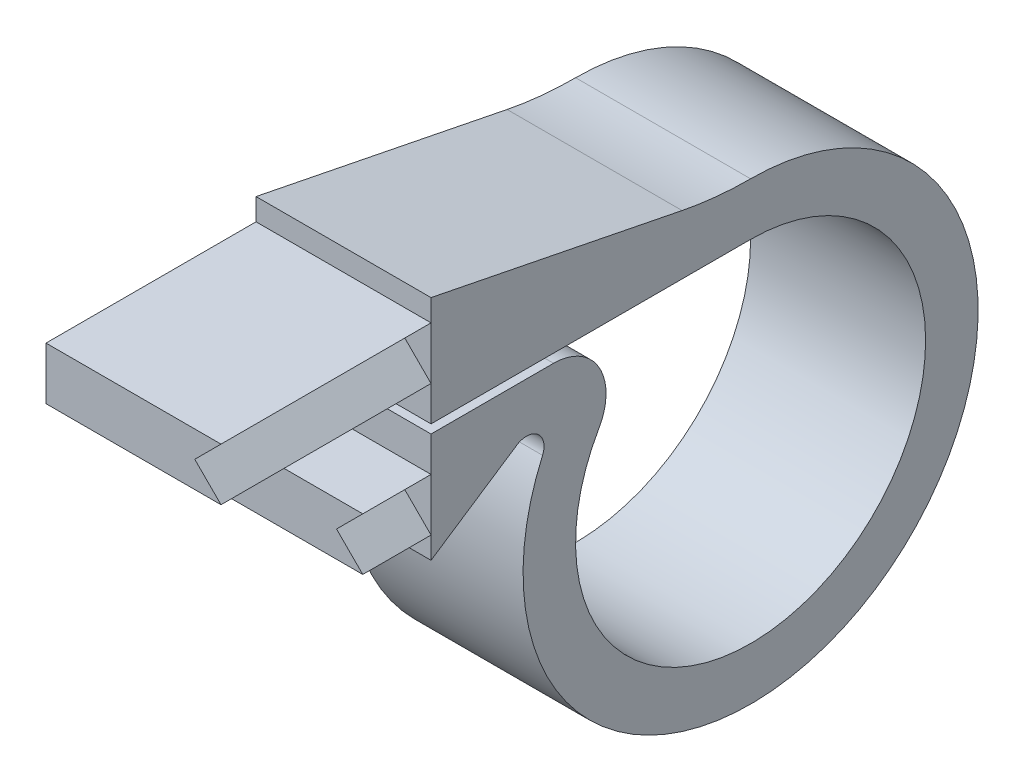
SolidWorks part; units mm, degrees
ref_plane "Front Plane" through (0, 0, 0) normal (0, 0, 1) x (1, 0, 0)
ref_plane "Top Plane" through (0, 0, 0) normal (0, 1, 0) x (1, 0, 0)
ref_plane "Right Plane" through (0, 0, 0) normal (1, 0, 0) x (0, 0, -1)
sketch "Sketch1" plane through (0, 0, 0) normal (1, 0, 0) x (0, 0, -1)
  line L0 (-11.2583, -0.5) -> (-18.2583, -0.5)
  line L1 (0, 0) -> (-18.2583, 0)
  line L6 (-3.915, 3.3869) -> (-18.2583, 6.25)
  line L7 (-18.2583, 6.25) -> (-18.2583, 0)
  line L9 (-18.2583, -6.75) -> (-13.3544, -3.5)
  line L10 (-18.2583, -6.75) -> (-18.2583, -0.5)
  arc A0 (0, 0) -> (-8.6603, -5) centre (0, -10) cw
  arc A1 (0, 3) -> (-11.8876, -4.7383) centre (0, -10) cw
  arc A2 (-8.6603, -5) -> (-11.2583, -0.5) centre (-11.2583, -3.5) ccw
  arc A3 (-11.8876, -4.7383) -> (-13.3544, -3.5) centre (-12.802, -4.3336) ccw
  arc A4 (0, 3) -> (-3.915, 3.3869) centre (0, 23) cw
  dimension "D1" = 3
  dimension "D4" = 3
  dimension "D5" = 1
  dimension "D6" = 10
  dimension "D3" = 20
  dimension "D11" = 3
  dimension "D2" = 7
  dimension "D7" = 0.5
  dimension "D8" = 6.25
  dimension "D9" = 6.25
  dimension "D10" = 3
extrude "Boss-Extrude1" add sketch "Sketch1" along normal blind 10
sketch "Sketch2" plane through (0, 0, 18.2583) normal (0, 0, 1) x (1, 0, 0)
  line L2 (10, -0.5) -> (10, -6.75) construction
  line L3 (10, 6.25) -> (10, 0) construction
  line L5 (10, -0.5) -> (0, -0.5) construction
  line L6 (0, 2) -> (10, 2)
  line L7 (0, 6.25) -> (0, 0) construction
  line L8 (0, -0.5) -> (0, -6.75) construction
  line L11 (10, 5) -> (0, 5)
  line L12 (0, 5) -> (0, 2)
  line L14 (10, 5) -> (8.5, 3.5)
  line L15 (8.5, 3.5) -> (10, 2)
  line L16 (10, 0) -> (0, 0) construction
  line L17 (0, -5.5) -> (10, -5.5)
  line L18 (10, -2.5) -> (0, -2.5)
  line L19 (0, -2.5) -> (0, -5.5)
  line L20 (10, -2.5) -> (8.5, -4)
  line L21 (8.5, -4) -> (10, -5.5)
  point P10 (0, 3.5)
  point P12 (0, -4)
  dimension "D1" = 3
  dimension "D2" = 3
  dimension "D4" = 3
  dimension "D6" = 2
  dimension "D7" = 2
extrude "Boss-Extrude4" add sketch "Sketch2" along normal blind 12
sketch "Sketch6" plane through (0, 0, 0) normal (-1, 0, 0) x (0, 0, 1)
  line L0 (18.2583, -2.5) -> (18.2583, -5.5)
  line L1 (18.2583, -5.5) -> (22.1583, -5.5)
  line L2 (30.2583, -5.5) -> (18.2583, -5.5) construction
  line L3 (22.1583, -5.5) -> (22.1583, -2.5)
  line L4 (30.2583, -2.5) -> (18.2583, -2.5) construction
  line L5 (22.1583, -2.5) -> (30.2583, -2.5)
  line L6 (30.2583, -2.5) -> (30.2583, -5.5)
  line L7 (30.2583, -2.5) -> (30.2583, -5.5) construction
  line L8 (30.2583, -5.5) -> (22.1583, -5.5)
  line M15 (18.2583, -5.5) -> (30.2583, -5.5)
  line M16 (30.2583, -5.5) -> (30.2583, -2.5)
  line M17 (30.2583, -2.5) -> (18.2583, -2.5)
  dimension "D1" = 3.9
extrude "Cut-Extrude2" cut sketch "Sketch6" against normal blind 12 contours L3 M15 M16 M17
